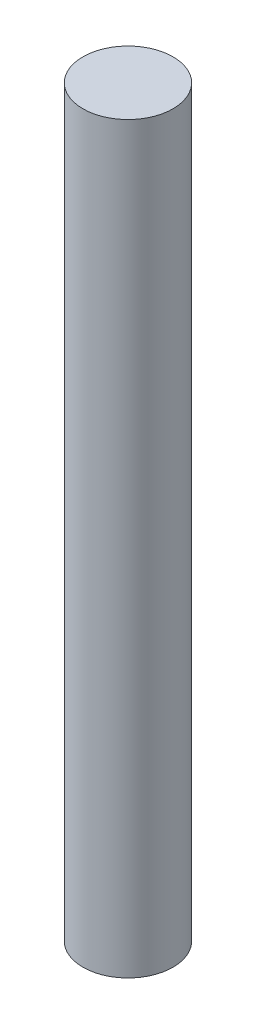
SolidWorks part; units mm, degrees
material "Chrome Stainless Steel"
ref_plane "Front Plane" through (0, 0, 0) normal (0, 0, 1) x (1, 0, 0)
ref_plane "Top Plane" through (0, 0, 0) normal (0, 1, 0) x (1, 0, 0)
ref_plane "Right Plane" through (0, 0, 0) normal (1, 0, 0) x (0, 0, -1)
sketch "Sketch1" plane through (0, 0, 0) normal (0, 1, 0) x (1, 0, 0)
  circle A0 centre (0, 0) radius 2
  dimension "D1" = 4
extrude "Boss-Extrude1" add sketch "Sketch1" along normal blind 33
